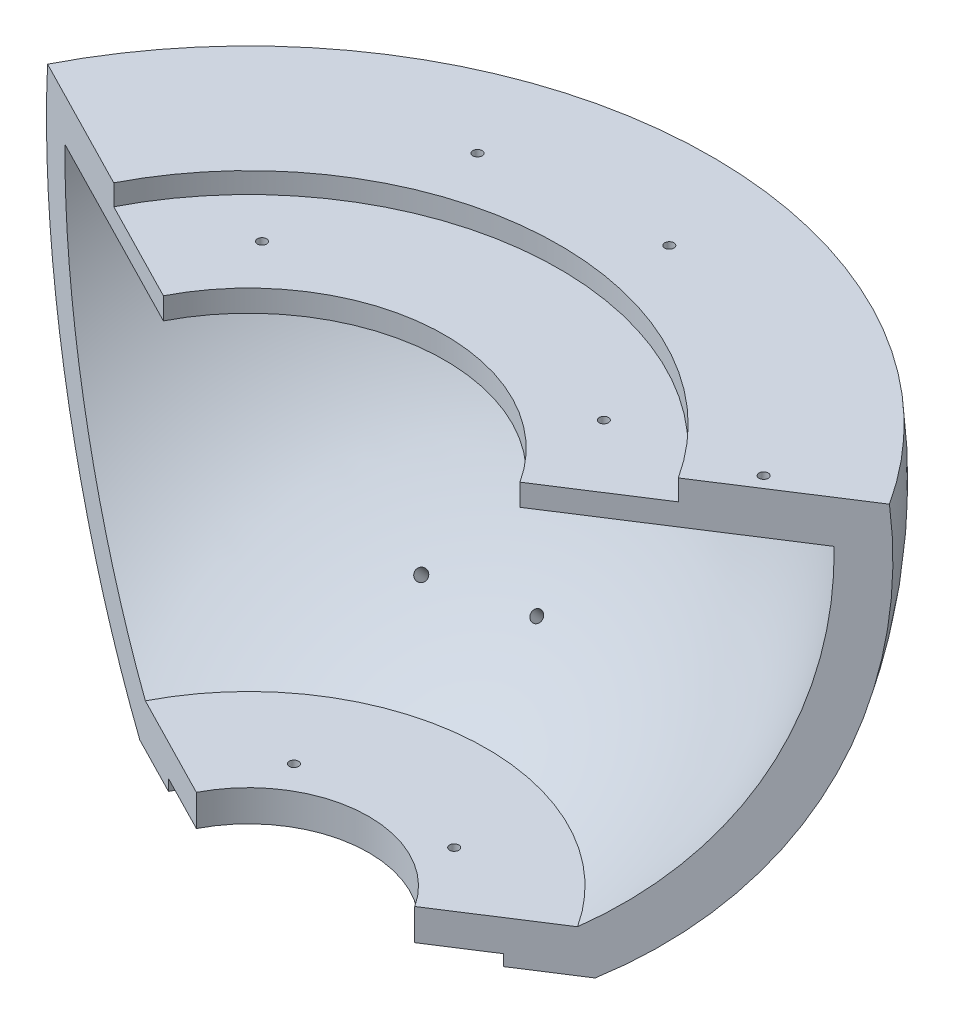
SolidWorks part; units mm, degrees
ref_plane "Plan de face" through (0, 0, 0) normal (0, 0, 1) x (1, 0, 0)
ref_plane "Plan de dessus" through (0, 0, 0) normal (0, 1, 0) x (1, 0, 0)
ref_plane "Plan de droite" through (0, 0, 0) normal (1, 0, 0) x (0, 0, -1)
sketch "Esquisse1" plane through (0, 0, 0) normal (0, 0, 1) x (1, 0, 0)
  line L0 (62.652, -45.2683) -> (117.5387, 212.9533) construction
  line L1 (0.3341, -92.6254) -> (0.3341, 171)
  line L2 (0, -110) -> (0, -296.0954) construction
  line L3 (0.3341, -92.6254) -> (59.3341, -92.6254)
  line L4 (0.3341, -92.6254) -> (0.3341, -77.5539) construction
  line L5 (0, 130.8616) -> (102, 130.8616) construction
  arc A0 (59.3341, -92.6254) -> (109.3586, 11.8616) centre (0, 0) ccw
  arc A1 (102, 130.8616) -> (83, 190.149) centre (0, 130.8616) ccw
  arc A3 (83, 190.149) -> (0.3341, 171) centre (15.1332, 295.1209) cw
  spline S0 degree 3 poles (102, 130.8616) (103.479, 113.6847) (71.2053, 65.5607) (110.7074, 34.2525) (109.3586, 11.8616) knots 0 0 0 0 0.406613 1 1 1 1
  dimension "D1" = 220
  dimension "D2" = 130.8616
  dimension "D3" = 102
  dimension "D8" = 12
  dimension "D9" = 110
  dimension "D12" = 59
  dimension "D13" = 281.0002
  dimension "D14" = 125
  dimension "D15" = 110
  dimension "D4" = 119
  dimension "D5" = 90
  dimension "D6" = 106
  dimension "D7" = 54
  dimension "D10" = 281
  dimension "D11" = 83
  dimension "D16" = 102
  dimension "D17" = 104.4869
revolve "Révolution2" add sketch "Esquisse1" angle 360 about L1
sketch "Esquisse2" plane through (0, 0, 0) normal (0, 1, 0) x (1, 0, 0)
  line L0 (0.3341, 0) -> (-105.6003, 54.3362) construction
  line L1 (0.3341, 0) -> (98.5184, 63.3863) construction
  line L2 (0.3341, 0) -> (6.0228, -114.443) construction
  dimension "D1" = 120
  dimension "D2" = 120
sketch "Esquisse3" plane through (0, 0, 0) normal (0, 1, 0) x (1, 0, 0)
  line L0 (0.3341, 0) -> (-105.6003, 54.3362) construction
  line L1 (0.3341, 0) -> (98.5184, 63.3863) construction
  line L2 (-97.2444, 50.0502) -> (0.3341, 0)
  line L3 (0.3341, 0) -> (92.4682, 59.4804)
  arc A0 (-97.2444, 50.0502) -> (92.4682, 59.4804) centre (0.3341, 0) ccw
  circle A1 centre (0.3341, 0) radius 109.6659 construction
extrude "Enlèv. mat.-Extru.1" cut sketch "Esquisse3" against normal mid plane 410
sketch "Esquisse4" plane through (0, 0, 0) normal (0, 0, 1) x (1, 0, 0)
  line L1 (107.6727, 198.162) -> (-111.7488, 198.162)
  line L2 (107.6727, 198.162) -> (107.6727, 11.3746)
  line L3 (107.6727, 11.3746) -> (-111.7488, 11.3746)
  line L4 (-111.7488, 198.162) -> (-111.7488, 11.3746)
  line L5 (-52.1629, -92.6254) -> (49.9021, -92.6254) construction
  dimension "D1" = 104
extrude "Enlèv. mat.-Extru.2" cut sketch "Esquisse4" against normal through all
shell "Coque2" thickness 10
ref_plane "Plan1" through (0, 11.5, 0) normal (0, 1, 0) x (1, 0, 0)
sketch "Esquisse6" plane through (0, 11.5, 0) normal (0, 1, 0) x (1, 0, 0)
  line L0 (0.3341, 0) -> (-105.6003, 54.3362) construction
  line L1 (0.3341, 0) -> (98.5184, 63.3863) construction
  line L2 (-64.7515, 33.3839) -> (0.3341, 0)
  line L3 (0.3341, 0) -> (61.7882, 39.6739)
  arc A0 (-64.7515, 33.3839) -> (61.7882, 39.6739) centre (0.3341, 0) cw
  dimension "D1" = 73.1479
extrude "Enlèv. mat.-Extru.4" cut sketch "Esquisse6" against normal blind 5
sketch "Esquisse7" plane through (0, 11.5, 0) normal (0, 1, 0) x (1, 0, 0)
  line L0 (0.3341, 0) -> (-105.6003, 54.3362) construction
  line L1 (0.3341, 0) -> (98.5184, 63.3863) construction
  line L2 (-40.7749, 21.0857) -> (0.3341, 0)
  line L3 (0.3341, 0) -> (39.1494, 25.0586)
  arc A0 (-40.7749, 21.0857) -> (39.1494, 25.0586) centre (0.3341, 0) cw
  dimension "D1" = 46.2013
extrude "Enlèv. mat.-Extru.5" cut sketch "Esquisse7" against normal blind 25
ref_plane "Plan2" through (0, -92.5, 0) normal (0, 1, 0) x (1, 0, 0)
sketch "Esquisse8" plane through (0, -92.5, 0) normal (0, 1, 0) x (1, 0, 0)
  line L0 (0.3341, 0) -> (98.5184, 63.3863) construction
  line L1 (0.3341, 0) -> (-105.6003, 54.3362) construction
  line L2 (36.8282, 23.56) -> (0.3341, 0)
  line L3 (0.3341, 0) -> (-38.3164, 19.8247)
  arc A0 (36.8282, 23.56) -> (-38.3164, 19.8247) centre (0.3341, 0) ccw
  dimension "D1" = 43.4383
extrude "Enlèv. mat.-Extru.6" cut sketch "Esquisse8" along normal mid plane 5
sketch "Esquisse10" plane through (0, -92.5, 0) normal (0, 1, 0) x (1, 0, 0)
  line L0 (0.3341, 0) -> (98.5184, 63.3863) construction
  line L1 (0.3341, 0) -> (-105.6003, 54.3362) construction
  line L2 (-24.8381, 12.9114) -> (0.3341, 0)
  line L3 (0.3341, 0) -> (24.1019, 15.3441)
  arc A0 (24.1019, 15.3441) -> (-24.8381, 12.9114) centre (0.3341, 0) ccw
  dimension "D1" = 28.2904
extrude "Enlèv. mat.-Extru.10" cut sketch "Esquisse10" along normal blind 15
scale "Echelle1" scale about centroid uniform scaling yes scale factor 1.15
sketch "Esquisse12" plane through (0, -98.6068, 0) normal (0, -1, 0) x (1, 0, 0)
  line L0 (-0.9377, -25.586) -> (-1.615, -39.212) construction
  line L1 (0.8656, 10.692) -> (-21.5644, -24.0517) construction
  line L2 (-40.6646, -65.1026) -> (-48.4635, -65.1026) construction
  line L3 (0.8656, 10.692) -> (19.7396, -26.1048) construction
  line L4 (0.3341, 0) -> (6.0228, 114.443) construction
  circle A0 centre (-21.5644, -24.0517) radius 1.25
  arc A1 (-43.5831, -12.118) -> (42.8332, -16.4135) centre (0.8651, 10.6805) ccw construction
  circle A2 centre (19.7396, -26.1048) radius 1.25
  circle A4 centre (-1.1875, -30.612) radius 1.25
  circle A7 centre (0.8656, 10.692) radius 41.355 construction
  point P1 (-1.615, -39.212)
  dimension "D1" = 2.5
  dimension "D5" = 30
  dimension "D3" = 8.6
  dimension "D6" = 30
  dimension "D2" = 2.5
  dimension "D4" = 82.71
hole_wizard "Trou taraudé M32" positions "Esquisse3D2" profile "Esquisse14" tap size "M3" standard "Iso"
sketch3d "Esquisse3D2"
  point P0 (-21.5644, -98.6068, -24.0517)
  point P6 (19.7396, -98.6068, -26.1048)
sketch "Esquisse14" plane through (-21.5644, -98.6068, -24.0517) normal (1, 0, 0) x (0, 0, -1)
  line L0 (0, 0) -> (0, 13.2511)
  line L1 (0, 13.2511) -> (1.25, 12.5)
  line L2 (1.25, 12.5) -> (1.25, 0)
  line L5 (1.25, 0) -> (0, 0)
  line L10 (0, 13.2511) -> (-1.25, 12.5) construction
  line L11 (0, -6.35) -> (0, 107.95) construction
  dimension "Diamètre du trou pour taraudage" = 2.5
  dimension "Profondeur du trou pour taraudage" = 12.5
  dimension "Angle de pointe" = 118
sketch "Esquisse15" plane through (0, 12.3682, 0) normal (0, 1, 0) x (1, 0, 0)
  line L0 (-73.9834, 27.7109) -> (-46.4103, 13.5681) construction
  line L1 (45.5026, 18.1369) -> (71.5372, 34.9444) construction
  line L2 (-1.7727, 42.3855) -> (-3.3112, 73.3359) construction
  line L3 (-45.8023, 39.6351) -> (0.8651, -10.6805) construction
  line L4 (42.3125, 44.0151) -> (0.8651, -10.6805) construction
  circle A0 centre (0.8651, -10.6805) radius 68.6258 construction
  arc A2 (45.5026, 18.1369) -> (-46.4103, 13.5681) centre (0.8651, -10.6805) ccw construction
  circle A3 centre (-2.542, 57.8607) radius 1.25
  circle A4 centre (42.3125, 44.0151) radius 1.25
  circle A5 centre (-45.8023, 39.6351) radius 1.25
  arc A6 (71.5372, 34.9444) -> (-73.9834, 27.7109) centre (0.8651, -10.6805) ccw construction
  point P0 (-60.1968, 20.6395)
  point P1 (58.5199, 26.5406)
  point P8 (-2.542, 57.8607)
  point P17 (-2.542, 57.8607)
  point P18 (-2.542, 57.8607)
  dimension "D1" = 2.5
  dimension "D2" = 40
  dimension "D3" = 40
hole_wizard "Trou taraudé M33" positions "Esquisse3D3" profile "Esquisse16" tap size "M3" standard "Iso"
sketch3d "Esquisse3D3"
  point P0 (-45.8023, 12.3682, -39.6351)
  point P6 (42.3125, 12.3682, -44.0151)
sketch "Esquisse16" plane through (-45.8023, 12.3682, -39.6351) normal (1, 0, 0) x (0, 0, 1)
  line L0 (0, 0) -> (0, 13.2511)
  line L1 (0, 13.2511) -> (1.25, 12.5)
  line L2 (1.25, 12.5) -> (1.25, 0)
  line L5 (1.25, 0) -> (0, 0)
  line L10 (0, 13.2511) -> (-1.25, 12.5) construction
  line L11 (0, -6.35) -> (0, 107.95) construction
  dimension "Diamètre du trou pour taraudage" = 2.5
  dimension "Profondeur du trou pour taraudage" = 12.5
  dimension "Angle de pointe" = 118
sketch "Esquisse17" [suppressed] plane through (0, 17.974, 0) normal (0, 1, 0) x (1, 0, 0)
  line L0 (-5.3625, 114.6024) -> (-4.1198, 89.6024) construction
  line L1 (-61.759, 67.8063) -> (0.8656, -10.692) construction
  line L2 (0.8656, -10.692) -> (37.5348, 82.7917) construction
  line L3 (-14.1198, 88.6018) -> (0.8656, -10.692) construction
  line L5 (0.3341, 0) -> (6.0228, -114.443) construction
  circle A0 centre (0.8656, -10.692) radius 100.4183 construction
  circle A2 centre (-14.1198, 88.6018) radius 1.5
  circle A3 centre (-61.759, 67.8063) radius 1.5
  circle A4 centre (37.5348, 82.7917) radius 1.5
  arc A5 (106.2495, 57.3541) -> (-110.7469, 46.5678) centre (0.8651, -10.6805) ccw construction
  point P5 (-31.9601, 191.6266)
  point P6 (-31.9601, 166.6266)
  point P15 (-38.1876, 191.5028)
  dimension "D2" = 3
  dimension "D1" = 25
  dimension "D3" = 10
  dimension "D4" = 30
  dimension "D5" = 30
hole_wizard "Trou taraudé M34" [suppressed] positions "Esquisse3D4" profile "Esquisse18" tap size "M3" standard "Iso"
sketch3d "Esquisse3D4" [suppressed]
  point P0 (-61.759, 17.974, -67.8063)
  point P6 (37.5348, 17.974, -82.7917)
  point P10 (-14.1198, 17.974, -88.6018)
sketch "Esquisse18" plane through (-61.759, 17.974, -67.8063) normal (1, 0, 0) x (0, 0, 1)
  line L0 (0, 0) -> (0, 13.2511)
  line L1 (0, 13.2511) -> (1.25, 12.5)
  line L2 (1.25, 12.5) -> (1.25, 0)
  line L5 (1.25, 0) -> (0, 0)
  line L10 (0, 13.2511) -> (-1.25, 12.5) construction
  line L11 (0, -6.35) -> (0, 107.95) construction
  dimension "Diamètre du trou pour taraudage" = 2.5
  dimension "Profondeur du trou pour taraudage" = 12.5
  dimension "Angle de pointe" = 118
sketch "Esquisse20" plane through (0, 17.974, 0) normal (0, 1, 0) x (1, 0, 0)
  circle A0 centre (15.8397, 88.1919) radius 1.5819
  circle A1 centre (82.5393, 47.0197) radius 1.6414
sketch "Esquisse22" plane through (0, 17.974, 0) normal (0, 1, 0) x (1, 0, 0)
  circle A0 centre (-66.1624, 63.5309) radius 1.5993
  circle A1 centre (-31.7154, 83.8632) radius 1.7
  circle A2 centre (15.8397, 88.1919) radius 1.7
  circle A3 centre (53.3916, 74.4133) radius 1.7
  circle A4 centre (82.5393, 47.0197) radius 1.7124
hole_wizard "Trou taraudé M35" positions "Esquisse3D5" profile "Esquisse21" tap size "M3" standard "Iso"
sketch3d "Esquisse3D5"
  point P0 (82.5393, 17.974, -47.0197)
  point P3 (15.8397, 17.974, -88.1919)
  point P13 (-31.7154, 17.974, -83.8632)
sketch "Esquisse21" plane through (82.5393, 17.974, -47.0197) normal (1, 0, 0) x (0, 0, 1)
  line L0 (0, 0) -> (0, 13.2511)
  line L1 (0, 13.2511) -> (1.25, 12.5)
  line L2 (1.25, 12.5) -> (1.25, 0)
  line L5 (1.25, 0) -> (0, 0)
  line L10 (0, 13.2511) -> (-1.25, 12.5) construction
  line L11 (0, -6.35) -> (0, 107.95) construction
  dimension "Diamètre du trou pour taraudage" = 2.5
  dimension "Profondeur du trou pour taraudage" = 12.5
  dimension "Angle de pointe" = 118
sketch3d "Esquisse3D6"
  circle A0 centre (-34.1115, -87.2395, -81.3892) radius 1.25
  circle A1 centre (-8.8001, -87.2395, -87.3337) radius 1.25
  point P2 (-33.9159, -86.3281, -80.5564)
  point P5 (-8.6045, -86.3281, -86.5008)
  point P6 (-7.6366, -87.0937, -87.7665)
  point P7 (-9.1133, -86.3872, -88.1927)
  point P8 (-9.1156, -88.0178, -86.4078)
  point P9 (-9.9689, -87.3744, -86.9115)
  point P10 (-8.8001, -87.2395, -87.3337)
  point P11 (-34.1115, -87.2395, -81.3892)
  point P12 (-35.0726, -87.6563, -80.7074)
  point P13 (-34.0221, -86.4089, -82.3191)
ref_plane "Plan3" through (-19.2736, -89.8047, -82.0668) normal (-0.1565, -0.7291, -0.6663) x (-0.9877, 0.1155, 0.1056)
sketch "Esquisse23" plane through (-19.2736, -89.8047, -82.0668) normal (-0.1565, -0.7291, -0.6663) x (-0.9877, 0.1155, 0.1056)
  circle A0 centre (-10.6041, 5.6184) radius 1.5
  circle A1 centre (15.0229, 1.2303) radius 1.5
  dimension "D1" = 3
extrude "Enlèv. mat.-Extru.11" cut sketch "Esquisse23" against normal blind 40
